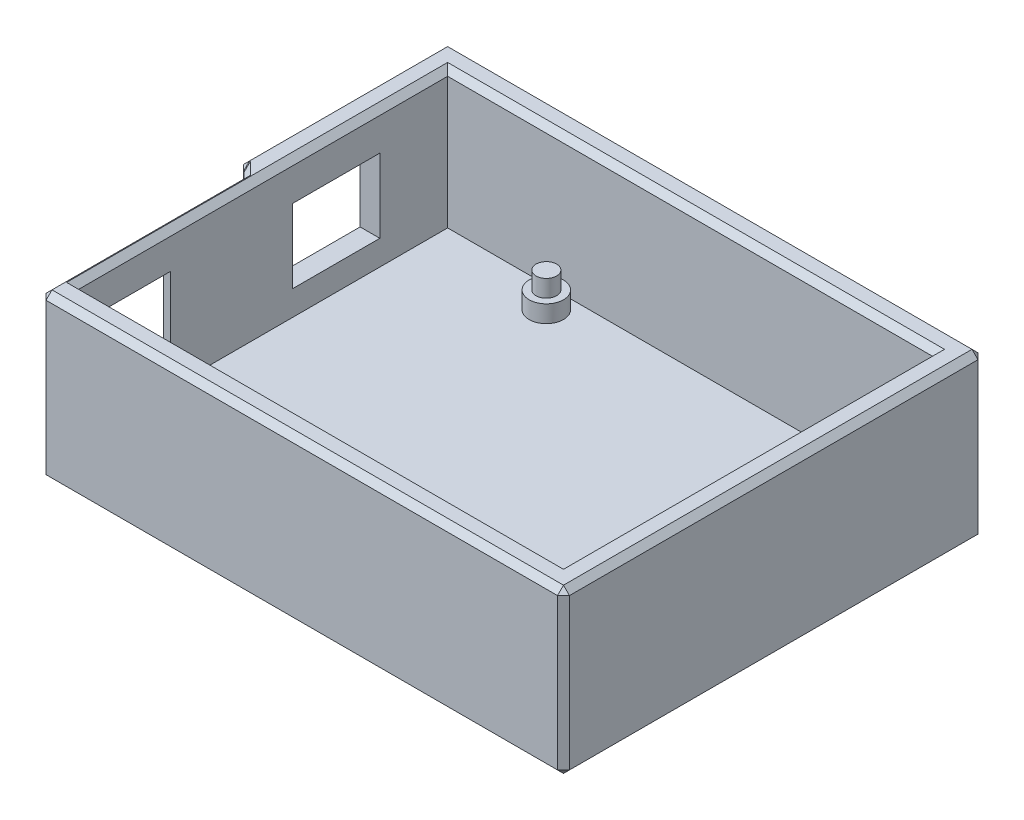
SolidWorks part; units mm, degrees
ref_plane "Front Plane" through (0, 0, 0) normal (0, 0, 1) x (1, 0, 0)
ref_plane "Top Plane" through (0, 0, 0) normal (0, 1, 0) x (1, 0, 0)
ref_plane "Right Plane" through (0, 0, 0) normal (1, 0, 0) x (0, 0, -1)
sketch "Sketch1" plane through (0, 0, 0) normal (0, 1, 0) x (1, 0, 0)
  line L1 (-39.6875, -31.115) -> (39.6875, -31.115)
  line L2 (-39.6875, -31.115) -> (-39.6875, 31.115)
  line L3 (-39.6875, 31.115) -> (39.6875, 31.115)
  line L4 (39.6875, -31.115) -> (39.6875, 31.115)
  line L5 (-39.6875, -31.115) -> (39.6875, 31.115) construction
  line L6 (-39.6875, 31.115) -> (39.6875, -31.115) construction
  point P0 (0, 0)
  dimension "D1" = 79.375
  dimension "D2" = 62.23
extrude "Boss-Extrude1" add sketch "Sketch1" against normal blind 24.13
shell "Shell1" thickness 3.81
ref_plane "Plane3" through (0, -17.78, 0) normal (0, 1, 0) x (-1, 0, 0)
ref_plane "Plane4" through (0, -15.24, 0) normal (0, 1, 0) x (-1, 0, 0)
sketch "riser base sketch" plane through (0, -20.32, 0) normal (0, 1, 0) x (1, 0, 0)
  line L0 (35.8775, 27.305) -> (-35.8775, 27.305) construction
  line L1 (35.8775, -27.305) -> (35.8775, 27.305) construction
  circle A0 centre (32.7025, 8.89) radius 2.54
  circle A1 centre (-18.0975, 24.13) radius 2.54
  circle A2 centre (-19.3675, -24.13) radius 2.54
  circle A3 centre (32.7025, -19.05) radius 2.54
  dimension "D1" = 52.07
  dimension "D6" = 5.08
  dimension "D7" = 5.08
  dimension "D8" = 5.08
  dimension "D9" = 5.08
  dimension "D2" = 5.08
  dimension "D3" = 27.94
  dimension "D4" = 50.8
  dimension "D5" = 15.24
  dimension "D10" = 3.175
  dimension "D11" = 3.175
extrude "Boss-Extrude3" add sketch "riser base sketch" along normal up to surface (2.54 mm away) up to plane "Plane3"
sketch "Sketch9" plane through (0, -17.78, 0) normal (0, 1, 0) x (-1, 0, 0)
  circle A0 centre (19.3675, 24.13) radius 1.524
  circle A1 centre (-32.7025, 19.05) radius 1.524
  circle A2 centre (-32.7025, -8.89) radius 1.524
  circle A3 centre (18.0975, -24.13) radius 1.524
  dimension "D1" = 3.048
  dimension "D2" = 3.048
  dimension "D3" = 3.048
  dimension "D4" = 3.048
extrude "Boss-Extrude4" add sketch "Sketch9" along normal up to surface (2.54 mm away) up to plane "Plane4"
sketch "Sketch10" plane through (-39.6875, 0, 0) normal (-1, 0, 0) x (0, 0, 1)
  line L0 (-17.145, -16.51) -> (-17.145, -5.842) construction
  line L1 (-17.272, -5.715) -> (-4.318, -5.715)
  line L2 (-17.272, -5.715) -> (-17.272, -16.637)
  line L3 (-17.272, -16.637) -> (-4.318, -16.637)
  line L4 (-4.318, -5.715) -> (-4.318, -16.637)
  line L5 (-17.145, -5.842) -> (-4.445, -5.842) construction
  line L6 (-4.445, -16.51) -> (-4.445, -5.842) construction
  line L7 (-17.145, -16.51) -> (-4.445, -16.51) construction
  dimension "D1" = 0.127
  dimension "D2" = 0.127
  dimension "D3" = 0.127
  dimension "D4" = 0.127
extrude "Cut-Extrude1" cut sketch "Sketch10" against normal up to surface (3.81 mm away) up to face at (-35.8775, -10.16, 0)
sketch "Sketch12" plane through (-39.6875, 0, 0) normal (-1, 0, 0) x (0, 0, 1)
  line L0 (13.86, -5.51) -> (13.86, -16.51) construction
  line L1 (13.733, -5.383) -> (22.987, -5.383)
  line L2 (13.733, -5.383) -> (13.733, -16.637)
  line L3 (13.733, -16.637) -> (22.987, -16.637)
  line L4 (22.987, -5.383) -> (22.987, -16.637)
  line L5 (22.86, -16.51) -> (22.86, -5.51) construction
  line L6 (22.86, -5.51) -> (13.86, -5.51) construction
  line L7 (13.86, -16.51) -> (22.86, -16.51) construction
  dimension "D1" = 0.127
  dimension "D2" = 0.127
  dimension "D3" = 0.127
  dimension "D4" = 0.127
extrude "Cut-Extrude2" cut sketch "Sketch12" against normal up to surface (3.81 mm away) up to face at (-35.8775, -11.176, -10.795)
sketch "Sketch13" plane through (-39.6875, 0, 0) normal (-1, 0, 0) x (0, 0, 1)
  line L0 (-31.115, -24.13) -> (31.115, -24.13) construction
  line L1 (31.115, -24.13) -> (0, -24.13)
  line L2 (31.115, -24.13) -> (31.115, 0)
  line L3 (31.115, 0) -> (0, 0)
  line L4 (0, -24.13) -> (0, 0)
  line L5 (31.115, -24.13) -> (31.115, 0) construction
  line L6 (-31.115, 0) -> (31.115, 0) construction
extrude "Cut-Extrude3" cut sketch "Sketch13" against normal up to vertex (1.905 mm away)
chamfer "Chamfer1" distance 0.889 angle 45 30 edges at (-39.6875, -16.637, -10.795) (-39.6875, -11.176, -4.318) (-39.6875, -5.715, -10.795) (-39.6875, -11.176, -17.272) (0, 0, -27.305) (-35.8775, 0, 0) (0, 0, 27.305) (35.8775, 0, 0) (0, -24.13, -31.115) (-39.6875, -24.13, -15.5575) (-39.6875, -12.065, -31.115) (39.6875, -12.065, -31.115) (39.6875, -24.13, 0) (-39.6875, 0, -15.5575) (0, 0, -31.115) (39.6875, 0, 0) (39.6875, -12.065, 31.115) (0.9525, -24.13, 31.115) (0.9525, 0, 31.115) (-37.7825, -24.13, 15.5575) (-38.735, -24.13, 0) (-39.6875, -12.065, 0) (-38.735, 0, 0) (-37.7825, 0, 15.5575) (-37.7825, -12.065, 31.115) (-37.7825, -16.637, 18.36) (-37.7825, -11.01, 22.987) (-37.7825, -5.383, 18.36) (-37.7825, -11.01, 13.733) (-37.7825, -12.065, 0)
